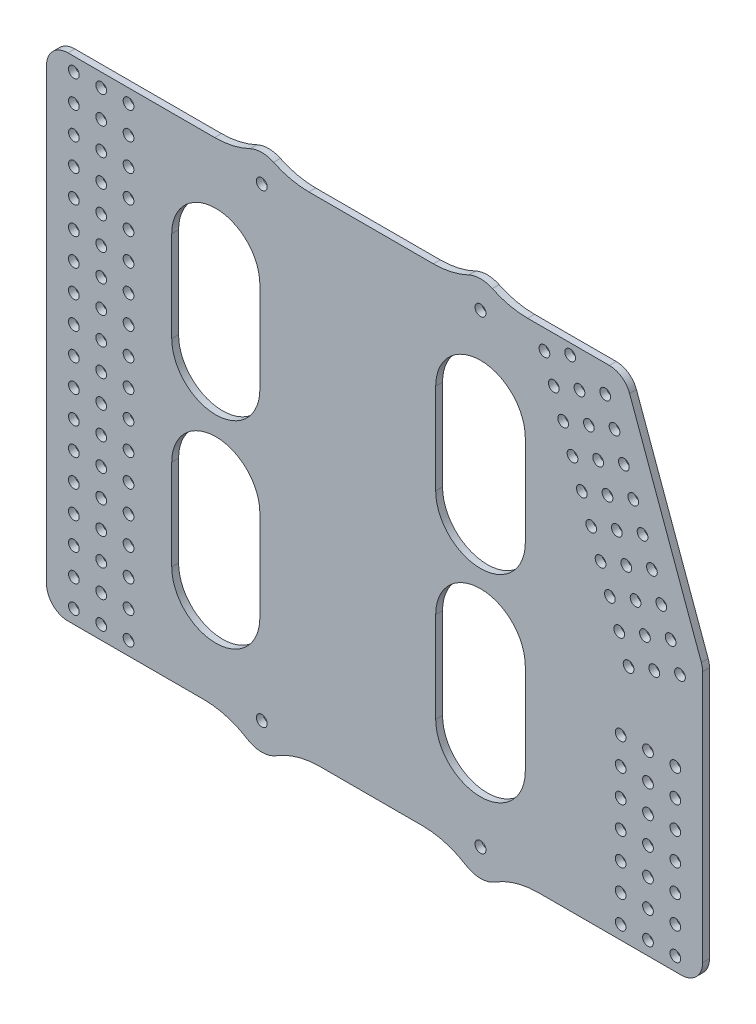
SolidWorks part; units mm, degrees
ref_plane "Front Plane" through (0, 0, 0) normal (0, 0, 1) x (1, 0, 0)
ref_plane "Top Plane" through (0, 0, 0) normal (0, 1, 0) x (1, 0, 0)
ref_plane "Right Plane" through (0, 0, 0) normal (1, 0, 0) x (0, 0, -1)
sketch "Sketch3" plane through (0, 0, 0) normal (0, 0, 1) x (1, 0, 0)
  line L0 (-62.0347, 275.0603) -> (206.4353, 275.0603)
  line L1 (204.6653, 90.9103) -> (204.6653, 78.2103) construction
  line L3 (206.4353, 275.0603) -> (242.7653, 175.2445)
  line L4 (242.7653, 175.2445) -> (242.7653, 46.4603)
  line L6 (242.7653, 46.4603) -> (-62.0347, 46.4603)
  line L7 (-62.0347, 46.4603) -> (-62.0347, 275.0603)
  line L8 (-49.3347, 268.7103) -> (-36.6347, 268.7103) construction
  line L9 (-49.3347, 268.7103) -> (-49.3347, 256.0103) construction
  line L10 (105.1393, -854.8604) -> (105.1393, 49145.1396) construction
  line L11 (169.2687, 265.7779) -> (173.6123, 253.8438) construction
  line L12 (204.6653, 129.0103) -> (204.6653, 116.3103) construction
  line L13 (23.6016, 116.2566) -> (23.6016, 141.6566) construction
  line L14 (23.6016, 185.8526) -> (23.6016, 211.2526) construction
  line L15 (-894.8607, 145.1396) -> (49105.1393, 145.1396) construction
  circle A0 centre (123.2241, 114.6088) radius 2.4892
  circle A1 centre (87.0545, 114.6088) radius 2.4892
  circle A2 centre (-49.3347, 268.7103) radius 2.4892
  circle A3 centre (-49.3347, 90.9103) radius 2.4892
  circle A4 centre (-36.6347, 268.7103) radius 2.4892
  circle A5 centre (-23.9347, 268.7103) radius 2.4892
  circle A6 centre (-36.6347, 256.0103) radius 2.4892
  circle A7 centre (-23.9347, 256.0103) radius 2.4892
  circle A8 centre (-36.6347, 243.3103) radius 2.4892
  circle A9 centre (-23.9347, 243.3103) radius 2.4892
  circle A10 centre (-36.6347, 230.6103) radius 2.4892
  circle A11 centre (-23.9347, 230.6103) radius 2.4892
  circle A12 centre (-36.6347, 217.9103) radius 2.4892
  circle A13 centre (-23.9347, 217.9103) radius 2.4892
  circle A14 centre (-36.6347, 205.2103) radius 2.4892
  circle A15 centre (-23.9347, 205.2103) radius 2.4892
  circle A16 centre (-36.6347, 192.5103) radius 2.4892
  circle A17 centre (-23.9347, 192.5103) radius 2.4892
  circle A18 centre (-36.6347, 179.8103) radius 2.4892
  circle A19 centre (-23.9347, 179.8103) radius 2.4892
  circle A20 centre (-36.6347, 167.1103) radius 2.4892
  circle A21 centre (-23.9347, 167.1103) radius 2.4892
  circle A22 centre (-36.6347, 154.4103) radius 2.4892
  circle A23 centre (-23.9347, 154.4103) radius 2.4892
  circle A24 centre (-36.6347, 141.7103) radius 2.4892
  circle A25 centre (-23.9347, 141.7103) radius 2.4892
  circle A26 centre (-36.6347, 129.0103) radius 2.4892
  circle A27 centre (-23.9347, 129.0103) radius 2.4892
  circle A28 centre (-36.6347, 116.3103) radius 2.4892
  circle A29 centre (-23.9347, 116.3103) radius 2.4892
  circle A30 centre (-36.6347, 103.6103) radius 2.4892
  circle A31 centre (-23.9347, 103.6103) radius 2.4892
  circle A32 centre (-36.6347, 90.9103) radius 2.4892
  circle A33 centre (-23.9347, 90.9103) radius 2.4892
  circle A34 centre (-49.3347, 256.0103) radius 2.4892
  circle A35 centre (-49.3347, 243.3103) radius 2.4892
  circle A36 centre (-49.3347, 230.6103) radius 2.4892
  circle A37 centre (-49.3347, 217.9103) radius 2.4892
  circle A38 centre (-49.3347, 205.2103) radius 2.4892
  circle A39 centre (-49.3347, 192.5103) radius 2.4892
  circle A40 centre (-49.3347, 179.8103) radius 2.4892
  circle A41 centre (-49.3347, 167.1103) radius 2.4892
  circle A42 centre (-49.3347, 154.4103) radius 2.4892
  circle A43 centre (-49.3347, 141.7103) radius 2.4892
  circle A44 centre (-49.3347, 129.0103) radius 2.4892
  circle A45 centre (-49.3347, 116.3103) radius 2.4892
  circle A46 centre (-49.3347, 103.6103) radius 2.4892
  circle A47 centre (-49.3347, 90.9103) radius 2.4892
  circle A48 centre (169.2687, 265.7779) radius 2.4892
  circle A49 centre (181.2028, 270.1215) radius 2.4892
  circle A50 centre (197.4805, 262.5311) radius 2.4892
  circle A51 centre (173.6123, 253.8438) radius 2.4892
  circle A52 centre (185.5464, 258.1874) radius 2.4892
  circle A53 centre (201.8242, 250.597) radius 2.4892
  circle A54 centre (177.956, 241.9097) radius 2.4892
  circle A55 centre (189.8901, 246.2533) radius 2.4892
  circle A56 centre (206.1678, 238.6629) radius 2.4892
  circle A57 centre (182.2996, 229.9756) radius 2.4892
  circle A58 centre (194.2337, 234.3192) radius 2.4892
  circle A59 centre (210.5115, 226.7288) radius 2.4892
  circle A60 centre (186.6433, 218.0415) radius 2.4892
  circle A61 centre (198.5774, 222.3851) radius 2.4892
  circle A62 centre (214.8551, 214.7947) radius 2.4892
  circle A63 centre (190.9869, 206.1074) radius 2.4892
  circle A64 centre (202.921, 210.451) radius 2.4892
  circle A65 centre (219.1988, 202.8606) radius 2.4892
  circle A66 centre (195.3306, 194.1733) radius 2.4892
  circle A67 centre (207.2647, 198.5169) radius 2.4892
  circle A68 centre (223.5424, 190.9265) radius 2.4892
  circle A69 centre (199.6743, 182.2392) radius 2.4892
  circle A70 centre (211.6083, 186.5828) radius 2.4892
  circle A71 centre (227.8861, 178.9924) radius 2.4892
  circle A72 centre (204.0179, 170.3051) radius 2.4892
  circle A73 centre (215.952, 174.6488) radius 2.4892
  circle A74 centre (232.2298, 167.0583) radius 2.4892
  circle A75 centre (208.3616, 158.371) radius 2.4892
  circle A76 centre (220.2957, 162.7147) radius 2.4892
  circle A78 centre (236.5734, 155.1242) radius 2.4892 [skipped]
  circle A79 centre (204.6653, 129.0103) radius 2.4892
  circle A80 centre (217.3653, 129.0103) radius 2.4892
  circle A81 centre (230.0653, 129.0103) radius 2.4892
  circle A82 centre (204.6653, 116.3103) radius 2.4892
  circle A83 centre (217.3653, 116.3103) radius 2.4892
  circle A84 centre (230.0653, 116.3103) radius 2.4892
  circle A85 centre (204.6653, 103.6103) radius 2.4892
  circle A86 centre (217.3653, 103.6103) radius 2.4892
  circle A87 centre (230.0653, 103.6103) radius 2.4892
  circle A88 centre (204.6653, 90.9103) radius 2.4892
  circle A89 centre (217.3653, 90.9103) radius 2.4892
  circle A90 centre (230.0653, 90.9103) radius 2.4892
  circle A91 centre (23.6016, 185.8526) radius 14.2875
  circle A92 centre (52.1422, 151.0564) radius 14.2875
  circle A93 centre (23.6016, 116.2566) radius 14.2875
  circle A94 centre (105.1393, 145.1396) radius 14.2875
  circle A95 centre (104.9447, 224.8273) radius 14.2875
  circle A96 centre (144.1424, 181.3926) radius 14.2875
  circle A99 centre (85.284, 241.0108) radius 2.4892
  circle A100 centre (23.6016, 141.6566) radius 2.4892
  circle A101 centre (45.5987, 128.9566) radius 2.4892
  circle A102 centre (45.5987, 103.5566) radius 2.4892
  circle A103 centre (23.6016, 90.8566) radius 2.4892
  circle A104 centre (1.6046, 103.5566) radius 2.4892
  circle A105 centre (1.6046, 128.9566) radius 2.4892
  circle A106 centre (23.6016, 211.2526) radius 2.4892
  circle A107 centre (45.5987, 198.5526) radius 2.4892
  circle A108 centre (45.5987, 173.1526) radius 2.4892
  circle A109 centre (23.6016, 160.4526) radius 2.4892
  circle A110 centre (1.6046, 173.1526) radius 2.4892
  circle A111 centre (1.6046, 198.5526) radius 2.4892
  circle A112 centre (123.2241, 175.6704) radius 2.4892
  circle A113 centre (87.0545, 175.6704) radius 2.4892
  circle A116 centre (124.6065, 208.849) radius 2.4892
  circle A117 centre (-49.3347, 78.2103) radius 2.4892
  circle A118 centre (-36.6347, 78.2103) radius 2.4892
  circle A119 centre (-23.9347, 78.2103) radius 2.4892
  circle A120 centre (-49.3347, 65.5103) radius 2.4892
  circle A121 centre (-36.6347, 65.5103) radius 2.4892
  circle A122 centre (-23.9347, 65.5103) radius 2.4892
  circle A123 centre (-49.3347, 52.8103) radius 2.4892
  circle A124 centre (-36.6347, 52.8103) radius 2.4892
  circle A125 centre (-23.9347, 52.8103) radius 2.4892
  circle A126 centre (204.6653, 78.2103) radius 2.4892
  circle A127 centre (217.3653, 78.2103) radius 2.4892
  circle A128 centre (230.0653, 78.2103) radius 2.4892
  circle A129 centre (204.6653, 65.5103) radius 2.4892
  circle A130 centre (217.3653, 65.5103) radius 2.4892
  circle A131 centre (230.0653, 65.5103) radius 2.4892
  circle A132 centre (204.6653, 52.8103) radius 2.4892
  circle A133 centre (217.3653, 52.8103) radius 2.4892
  circle A134 centre (230.0653, 52.8103) radius 2.4892
  dimension "D1" = 4.9784
  dimension "D2" = 6.35
  dimension "D10" = 4.9784
  dimension "D11" = 4.9784
  dimension "D12" = 4.9784
  dimension "D15" = 4.9784
  dimension "D16" = 4.9784
  dimension "D17" = 4.9784
  dimension "D20" = 4.9784
  dimension "D21" = 28.575
  dimension "D22" = 28.575
  dimension "D23" = 28.575
  dimension "D24" = 28.575
  dimension "D25" = 28.575
  dimension "D26" = 28.575
  dimension "D27" = 12.7
  dimension "D28" = 4.9784
  dimension "D32" = 4.9784
  dimension "D35" = 4.9784
  dimension "D38" = 4.9784
  dimension "D5" = 3
  dimension "D7" = 12.7
  dimension "D8" = 12.7
  dimension "D9" = 228.6
  dimension "D14" = 12.7
  dimension "D19" = 12.7
  dimension "D29" = 25.4
  dimension "D31" = 25.4
  dimension "D33" = 6
  dimension "D34" = 25.4
  dimension "D36" = 18.0848
  dimension "D37" = 30.5308
  dimension "D39" = 19.6607
  dimension "D40" = 16.1835
  dimension "D41" = 12.7
  dimension "D42" = 15.9782
  dimension "D43" = 19.6618
  dimension "D6" = 15
  dimension "D13" = 10
  dimension "D18" = 4
  dimension "D30" = 6
extrude "Boss-Extrude3" add sketch "Sketch3" along normal blind 3.175
fillet "Fillet2" radius 10 5 edges at (-62.0347, 275.0603, 1.5875) (-62.0347, 46.4603, 1.5875) (242.7653, 46.4603, 1.5875) (242.7653, 175.2445, 1.5875) (206.4353, 275.0603, 1.5875)
sketch "Sketch5" plane through (0, 0, 3.175) normal (0, 0, 1) x (1, 0, 0)
  circle A0 centre (23.6016, 185.8526) radius 14.2875
  circle A1 centre (23.6016, 211.2526) radius 2.4892
  circle A2 centre (45.5987, 198.5526) radius 2.4892
  circle A3 centre (1.6046, 198.5526) radius 2.4892
  circle A4 centre (1.6046, 173.1526) radius 2.4892
  circle A5 centre (23.6016, 160.4526) radius 2.4892
  circle A6 centre (45.5987, 173.1526) radius 2.4892
  circle A7 centre (23.6016, 116.2566) radius 14.2875
  circle A8 centre (1.6046, 128.9566) radius 2.4892
  circle A9 centre (23.6016, 141.6566) radius 2.4892
  circle A10 centre (45.5987, 128.9566) radius 2.4892
  circle A11 centre (1.6046, 103.5566) radius 2.4892
  circle A12 centre (23.6016, 90.8566) radius 2.4892
  circle A13 centre (45.5987, 103.5566) radius 2.4892
  circle A14 centre (52.1422, 151.0564) radius 14.2875
  circle A15 centre (105.1393, 145.1396) radius 14.2875
  circle A16 centre (87.0545, 114.6088) radius 2.4892
  circle A17 centre (123.2241, 114.6088) radius 2.4892
  circle A18 centre (87.0545, 175.6704) radius 2.4892
  circle A19 centre (123.2241, 175.6704) radius 2.4892
  circle A20 centre (144.1424, 181.3926) radius 14.2875
  circle A21 centre (104.9447, 224.8273) radius 14.2875
  circle A22 centre (124.6065, 208.849) radius 2.4892
  circle A23 centre (85.284, 241.0108) radius 2.4892
extrude "Boss-Extrude5" add sketch "Sketch5" against normal blind 3.175
sketch "Sketch6" plane through (0, 0, 3.175) normal (0, 0, 1) x (1, 0, 0)
  line L0 (16.6029, 184.2341) -> (16.6029, 226.3723) construction
  line L3 (-3.8642, 184.2341) -> (-3.8642, 226.3723)
  line L4 (32.254, 159.3691) -> (143.252, 159.3691) construction
  line L5 (87.753, 159.3691) -> (87.753, 108.5741) construction
  line L6 (37.0701, 184.2341) -> (37.0701, 226.3723)
  line L9 (-62.0347, 265.0603) -> (-62.0347, 56.4603) construction
  line L10 (87.753, 268.0089) -> (87.753, 52.1089) construction
  line L11 (87.753, 159.3691) -> (276.8248, 159.3691) construction
  line L12 (139.5653, 184.2341) -> (139.5653, 226.3723) construction
  line L13 (118.7562, 184.2341) -> (118.7562, 226.3723)
  line L14 (160.3743, 184.2341) -> (160.3743, 226.3723)
  line L15 (139.5653, 134.504) -> (139.5653, 92.3658) construction
  line L16 (118.7562, 134.504) -> (118.7562, 92.3658)
  line L17 (160.3743, 134.504) -> (160.3743, 92.3658)
  line L18 (16.6029, 134.504) -> (16.6029, 92.3658) construction
  line L19 (-3.8642, 134.504) -> (-3.8642, 92.3658)
  line L20 (37.0701, 134.504) -> (37.0701, 92.3658)
  circle A4 centre (37.9653, 267.3191) radius 2.54
  circle A5 centre (139.5653, 267.3191) radius 2.54
  circle A6 centre (139.5653, 51.4191) radius 2.54
  circle A7 centre (37.9653, 51.4191) radius 2.54
  arc A8 (-3.8642, 184.2341) -> (37.0701, 184.2341) centre (16.6029, 184.2341) ccw
  arc A9 (37.0701, 226.3723) -> (-3.8642, 226.3723) centre (16.6029, 226.3723) ccw
  arc A10 (118.7562, 184.2341) -> (160.3743, 184.2341) centre (139.5653, 184.2341) ccw
  arc A11 (160.3743, 226.3723) -> (118.7562, 226.3723) centre (139.5653, 226.3723) ccw
  arc A12 (118.7562, 134.504) -> (160.3743, 134.504) centre (139.5653, 134.504) cw
  arc A13 (160.3743, 92.3658) -> (118.7562, 92.3658) centre (139.5653, 92.3658) cw
  arc A14 (-3.8642, 134.504) -> (37.0701, 134.504) centre (16.6029, 134.504) cw
  arc A15 (37.0701, 92.3658) -> (-3.8642, 92.3658) centre (16.6029, 92.3658) cw
  point P2 (16.6029, 205.3032)
  point P9 (139.5653, 205.3032)
  point P20 (139.5653, 113.4349)
  point P40 (16.6029, 113.4349)
  dimension "D4" = 5.08
  dimension "D5" = 5.08
  dimension "D3" = 110.998
  dimension "D6" = 101.6
  dimension "D7" = 100
  dimension "D8" = 215.9
  dimension "D9" = 215.9
extrude "Cut-Extrude1" cut sketch "Sketch6" against normal blind 3.175
sketch "Sketch7" plane through (0, 0, 3.175) normal (0, 0, 1) x (1, 0, 0)
  line L0 (-52.0347, 46.4603) -> (232.7653, 46.4603) construction
  line L1 (199.4332, 275.0603) -> (-52.0347, 275.0603) construction
  line L2 (16.0742, 275.0603) -> (59.8564, 275.0603)
  line L3 (117.6742, 275.0603) -> (161.4564, 275.0603)
  line L4 (112.6101, 46.4603) -> (166.5205, 46.4603)
  line L5 (11.0101, 46.4603) -> (64.9205, 46.4603)
  arc A0 (31.2265, 40.6544) -> (44.7041, 40.6544) centre (37.9653, 51.4191) ccw
  arc A1 (11.0101, 46.4603) -> (31.2265, 40.6544) centre (11.0101, 8.3603) cw
  arc A2 (44.7041, 40.6544) -> (64.9205, 46.4603) centre (64.9205, 8.3603) cw
  arc A3 (132.8265, 40.6544) -> (146.3041, 40.6544) centre (139.5653, 51.4191) ccw
  arc A4 (112.6101, 46.4603) -> (132.8265, 40.6544) centre (112.6101, 8.3603) cw
  arc A5 (146.3041, 40.6544) -> (166.5205, 46.4603) centre (166.5205, 8.3603) cw
  arc A6 (129.4973, 275.0603) -> (149.6332, 275.0603) centre (139.5653, 267.3191) ccw
  arc A7 (117.6742, 275.0603) -> (134.0925, 278.7794) centre (117.6742, 313.1603) ccw
  arc A8 (145.038, 278.7794) -> (161.4564, 275.0603) centre (161.4564, 313.1603) ccw
  arc A10 (27.8973, 275.0603) -> (48.0332, 275.0603) centre (37.9653, 267.3191) ccw
  arc A11 (43.438, 278.7794) -> (59.8564, 275.0603) centre (59.8564, 313.1603) ccw
  arc A12 (16.0742, 275.0603) -> (32.4925, 278.7794) centre (16.0742, 313.1603) ccw
  arc A13 (49.6572, 46.4603) -> (26.2734, 46.4603) centre (37.9653, 51.4191) ccw
  arc A14 (151.2572, 46.4603) -> (127.8734, 46.4603) centre (139.5653, 51.4191) ccw
  arc A15 (43.438, 278.7794) -> (32.4925, 278.7794) centre (37.9653, 267.3191) ccw
  arc A16 (145.038, 278.7794) -> (134.0925, 278.7794) centre (139.5653, 267.3191) ccw
  dimension "D1" = 25.4
  dimension "D2" = 38.1
  dimension "D3" = 38.1
  dimension "D4" = 25.4
  dimension "D5" = 38.1
  dimension "D6" = 25.4
  dimension "D7" = 38.1
extrude "Boss-Extrude6" add sketch "Sketch7" against normal up to surface (3.175 mm away) contours A11 A15 A12 L2 | A8 A16 A7 L3 | A0 A2 L5 A1 | A3 A5 L4 A4 up to face at (137.0253, 51.4191, 0)
